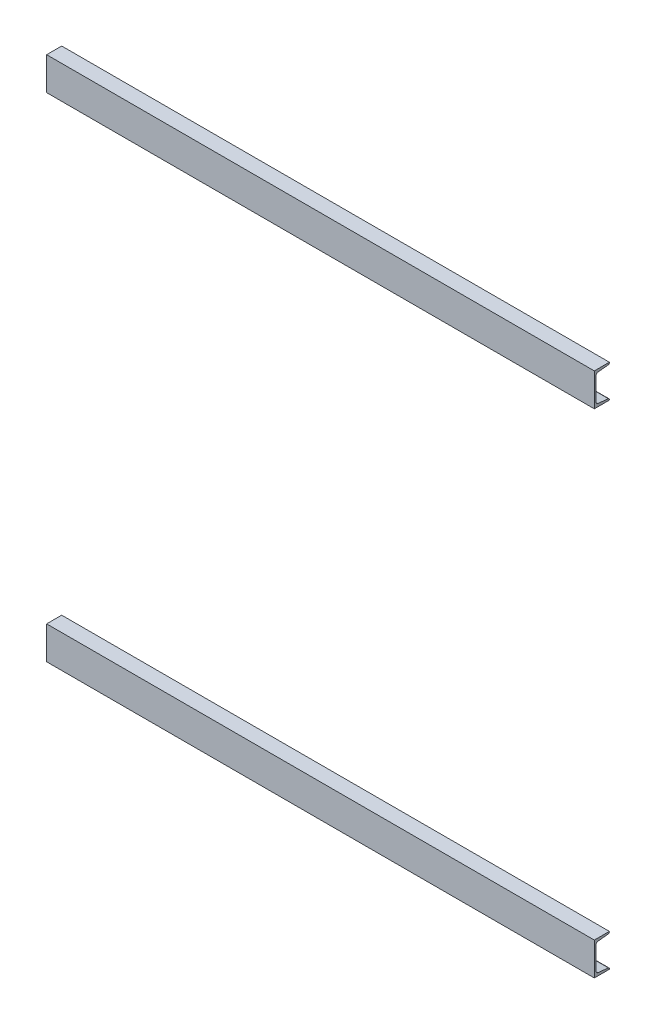
SolidWorks part; units mm, degrees
ref_plane "Alzado" through (0, 0, 0) normal (0, 0, 1) x (1, 0, 0)
ref_plane "Planta" through (0, 0, 0) normal (0, 1, 0) x (1, 0, 0)
ref_plane "Vista lateral" through (0, 0, 0) normal (1, 0, 0) x (0, 0, -1)
sketch "Croquis1" plane through (0, 0, 0) normal (0, 0, 1) x (1, 0, 0)
  line L1 (-1000, -900) -> (1000, -900)
  line L2 (-1000, -900) -> (-1000, 900)
  line L3 (-1000, 900) -> (1000, 900)
  line L4 (1000, -900) -> (1000, 900)
  line L5 (-1000, -900) -> (1000, 900) construction
  line L6 (-1000, 900) -> (1000, -900) construction
  point P0 (0, 0)
  dimension "D1" = 2000
  dimension "D2" = 1800
other "Miembro estructural1"
ref_plane "Plano1" through (-1000, 900, 0) normal (-1, 0, 0) x (0, 0, -1)
sketch "Sketch1" plane through (-1000, 900, 0) normal (-1, 0, 0) x (0, 0, -1)
  line L0 (55, 120) -> (0, 120)
  line L1 (55, 0) -> (0, 0)
  line L2 (0, 120) -> (0, 0)
  line L6 (55, 120) -> (55, 118.1136)
  line L7 (55, 0) -> (55, 1.8964)
  line L12 (6.3, 101.74) -> (6.3, 18.27)
  line L17 (13.4638, 109.6962) -> (50.9704, 113.6383)
  line L18 (13.4638, 10.3138) -> (50.9704, 6.3717)
  arc A0 (50.9704, 113.6383) -> (55, 118.1136) centre (50.5, 118.1136) ccw
  arc A1 (50.9704, 6.3717) -> (55, 1.8964) centre (50.5, 1.8964) cw
  arc A9 (6.3, 18.27) -> (13.4638, 10.3138) centre (14.3, 18.27) ccw
  arc A10 (6.3, 101.74) -> (13.4638, 109.6962) centre (14.3, 101.74) cw
  point P8 (0, 60)
  point P9 (6.3, 60.005)
  point P10 (27.5, 120)
  point P11 (27.5, 0)
  point P12 (55, 5.9482)
  point P13 (55, 114.0618)
  point P14 (0, 0)
  dimension "D4" = 4.5
  dimension "RI" = 8
  dimension "D2" = 6
  dimension "D3" = 18.26
  dimension "Depth" = 120
  dimension "BF" = 55
  dimension "TW" = 6.3
  dimension "d1" = 83.47
